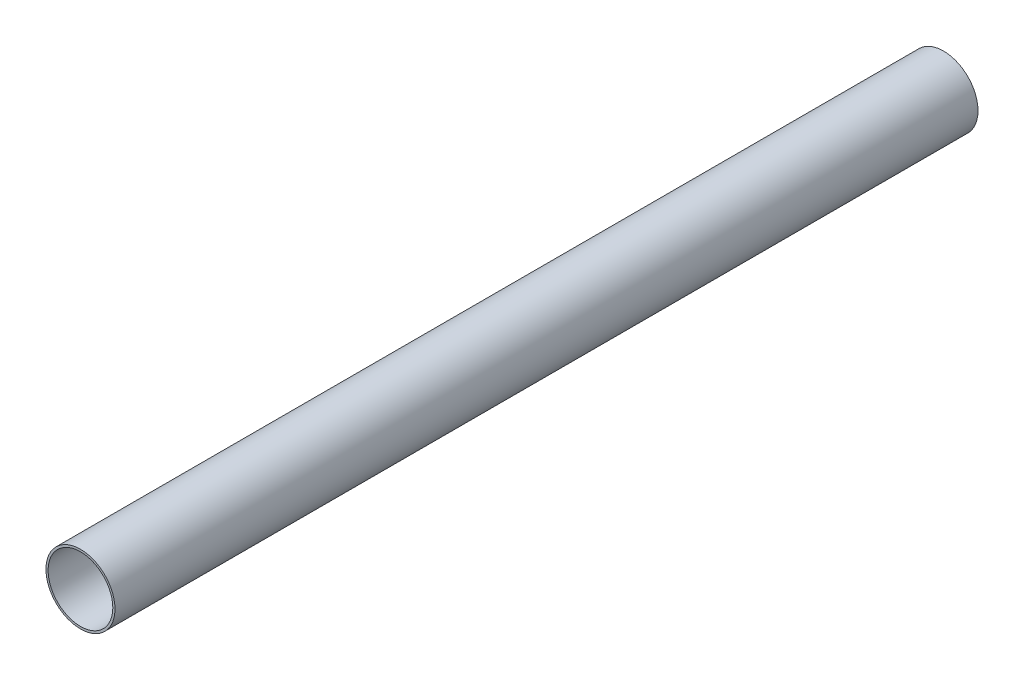
SolidWorks part; units mm, degrees
ref_plane "Front Plane" through (0, 0, 0) normal (0, 0, 1) x (1, 0, 0)
ref_plane "Top Plane" through (0, 0, 0) normal (0, 1, 0) x (1, 0, 0)
ref_plane "Right Plane" through (0, 0, 0) normal (1, 0, 0) x (0, 0, -1)
sketch "Sketch1" plane through (0, 0, 0) normal (0, 0, 1) x (1, 0, 0)
  circle A0 centre (0, 0) radius 16
  circle A1 centre (0, 0) radius 15
  dimension "D1" = 32
  dimension "D2" = 30
extrude "Boss-Extrude1" add sketch "Sketch1" along normal blind 400
